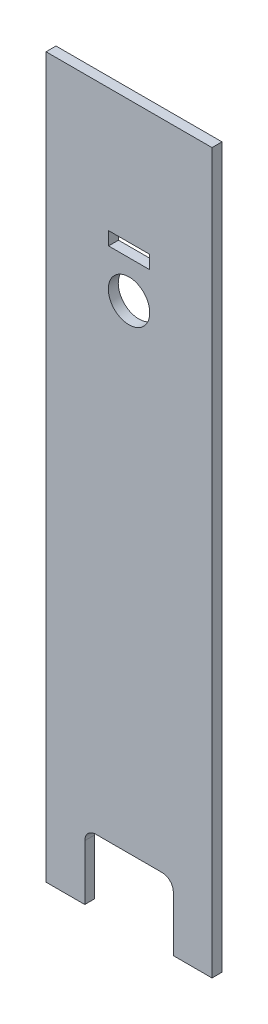
SolidWorks part; units mm, degrees
material "Faia"
ref_plane "Plano frontal" through (0, 0, 0) normal (0, 0, 1) x (1, 0, 0)
ref_plane "Plano superior" through (0, 0, 0) normal (0, 1, 0) x (1, 0, 0)
ref_plane "Plano direito" through (0, 0, 0) normal (1, 0, 0) x (0, 0, -1)
sketch "Esboço1" plane through (0, 0, 0) normal (0, 0, 1) x (1, 0, 0)
  line L0 (150, -650) -> (-150, 650) construction
  line L1 (-150, 650) -> (150, 650)
  line L2 (-150, 650) -> (-150, -650)
  line L3 (-150, -650) -> (150, -650)
  line L4 (150, 650) -> (150, -650)
  point P4 (0, 0)
  dimension "D1" = 1300
  dimension "D2" = 300
extrude "Ressalto-extrusão1" add sketch "Esboço1" along normal blind 18
sketch "Esboço2" plane through (0, 0, 0) normal (0, 0, -1) x (-1, 0, 0)
  line L0 (-150, -650) -> (150, -650) construction
  line L1 (-150, -650) -> (-150, 650) construction
  line L2 (-80, -650) -> (80, -650)
  line L3 (-80, -650) -> (-80, -550)
  line L4 (-60, -530) -> (60, -530)
  line L5 (80, -650) -> (80, -550)
  arc A0 (60, -530) -> (80, -550) centre (60, -550) cw
  arc A1 (-60, -530) -> (-80, -550) centre (-60, -550) ccw
  point P12 (80, -530)
  point P15 (-80, -530)
  dimension "D4" = 20
  dimension "D1" = 160
  dimension "D2" = 120
  dimension "D3" = 70
extrude "Corte-extrusão1" cut sketch "Esboço2" against normal through all
sketch "Esboço3" plane through (0, 0, 0) normal (0, 0, -1) x (-1, 0, 0)
  line L0 (-150, 650) -> (150, 650) construction
  line L1 (-150, 650) -> (150, 650)
  line L2 (-150, -650) -> (-150, 650) construction
  line L3 (-150, -650) -> (-150, 650)
  line L4 (-150, 650) -> (0, 650) construction
  line L5 (0, 650) -> (0, 335) construction
  circle A0 centre (0, 335) radius 37.5
  dimension "D1" = 75
  dimension "D2" = 315
extrude "Corte-extrusão2" cut sketch "Esboço3" against normal through all contours A0
sketch "Esboço4" plane through (0, 0, 18) normal (0, 0, 1) x (1, 0, 0)
  line L0 (0, 372.5) -> (0, 402.5) construction
  line L3 (-37, 402.5175) -> (37, 402.4825)
  line L4 (-37, 402.5175) -> (-37, 426.5175)
  line L5 (-37, 426.5175) -> (37, 426.5175)
  line L6 (37, 402.4825) -> (37, 426.5175)
  circle A1 centre (0, 335) radius 37.5 construction
  dimension "D1" = 30
  dimension "D2" = 24
  dimension "D3" = 74
extrude "Corte-extrusão3" cut sketch "Esboço4" against normal through all
